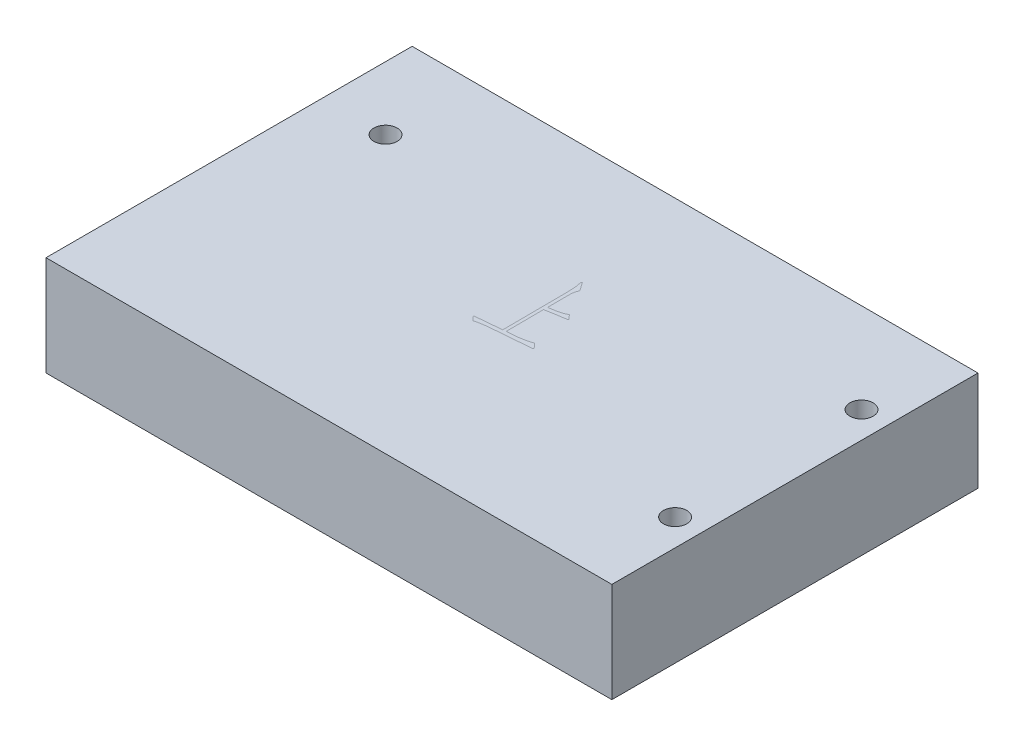
SolidWorks part; units mm, degrees
ref_plane "前视基准面" through (0, 0, 0) normal (0, 0, 1) x (1, 0, 0)
ref_plane "上视基准面" through (0, 0, 0) normal (0, 1, 0) x (1, 0, 0)
ref_plane "右视基准面" through (0, 0, 0) normal (1, 0, 0) x (0, 0, -1)
sketch "草图1" plane through (0, 0, 0) normal (0, 1, 0) x (1, 0, 0)
  line L1 (0, 0) -> (85, 0)
  line L2 (0, 0) -> (0, 55)
  line L3 (0, 55) -> (85, 55)
  line L4 (85, 0) -> (85, 55)
  circle A0 centre (81, 41.5) radius 1.75
  circle A1 centre (81, 13.5) radius 1.75
  circle A2 centre (9.5, 41.5) radius 1.75
  dimension "D3" = 3.5
  dimension "D4" = 4
  dimension "D5" = 13.5
  dimension "D6" = 28
  dimension "D7" = 9.5
  dimension "D1" = 85
  dimension "D2" = 55
extrude "凸台-拉伸1" add sketch "草图1" along normal blind 15
sketch "草图2" plane through (0, 15, 0) normal (0, 1, 0) x (1, 0, 0)
  text T0 "上" font "汉仪长仿宋体" height 10
split line "分割线1"
